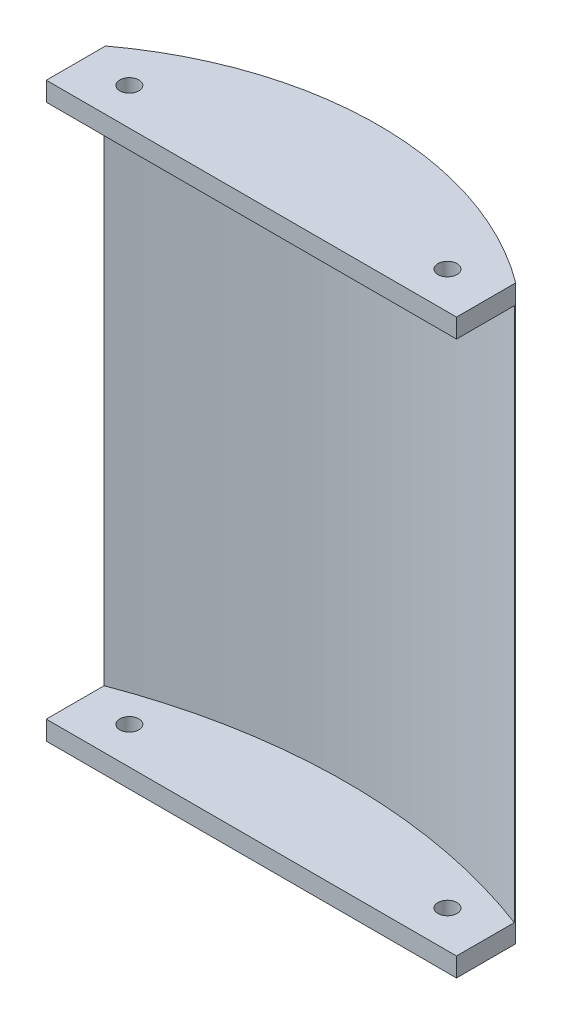
SolidWorks part; units mm, degrees
ref_plane "Plano frontal" through (0, 0, 0) normal (0, 0, 1) x (1, 0, 0)
ref_plane "Plano superior" through (0, 0, 0) normal (0, 1, 0) x (1, 0, 0)
ref_plane "Plano direito" through (0, 0, 0) normal (1, 0, 0) x (0, 0, -1)
sketch "Esboço1" plane through (0, 0, 0) normal (0, 1, 0) x (1, 0, 0)
  line L0 (0, 0) -> (64.5, 0)
  line L13 (64.5, 0) -> (64.5, 9.3121)
  line L14 (0, 0) -> (0, 9.3121)
  arc A2 (64.5, 9.3121) -> (0, 9.3121) centre (32.25, -34) ccw
extrude "Ressalto-extrusão1" add sketch "Esboço1" along normal blind 90 contours A2 L14 L0 L13
ref_plane "Plano2" through (32.25, 0, 0) normal (1, 0, 0) x (0, 0, -1)
sketch "Esboço3" plane through (32.25, 0, 0) normal (1, 0, 0) x (0, 0, -1)
  line L0 (-76, 87) -> (-76, 3)
  line L7 (15, 87) -> (-76, 87)
  line L9 (15, 87) -> (15, 3)
  line L13 (15, 3) -> (-76, 3)
sketch "Esboço4" plane through (0, 90, 0) normal (0, 1, 0) x (1, 0, 0)
  circle A0 centre (7.24, 5.82) radius 1.5
  circle A1 centre (57.26, 5.82) radius 1.5
revolve "Corte-Revolução2" cut sketch "Esboço3" angle 360 about L0
extrude "Corte-extrusão1" cut sketch "Esboço4" against normal through all
